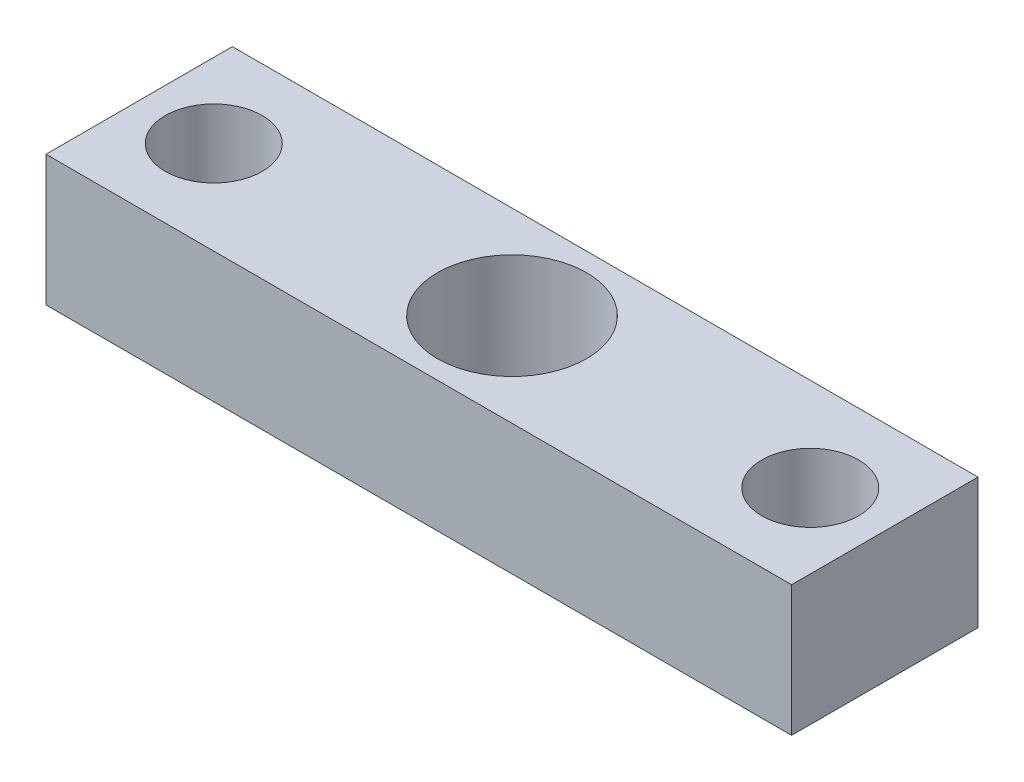
SolidWorks part; units mm, degrees
ref_plane "前视基准面" through (0, 0, 0) normal (0, 0, 1) x (1, 0, 0)
ref_plane "上视基准面" through (0, 0, 0) normal (0, 1, 0) x (1, 0, 0)
ref_plane "右视基准面" through (0, 0, 0) normal (1, 0, 0) x (0, 0, -1)
sketch "草图1" plane through (0, 0, 0) normal (0, 1, 0) x (1, 0, 0)
  line L1 (20, -5) -> (-20, -5)
  line L2 (20, -5) -> (20, 5)
  line L3 (20, 5) -> (-20, 5)
  line L4 (-20, -5) -> (-20, 5)
  line L5 (20, -5) -> (-20, 5) construction
  line L6 (20, 5) -> (-20, -5) construction
  circle A0 centre (-16, 0) radius 2.6
  circle A1 centre (16, 0) radius 2.6
  circle A2 centre (0, 0) radius 4
  point P0 (0, 0)
  dimension "D1" = 32
  dimension "D2" = 5.2
  dimension "D3" = 16
  dimension "D4" = 10
  dimension "D5" = 40
extrude "凸台-拉伸1" add sketch "草图1" along normal blind 7
